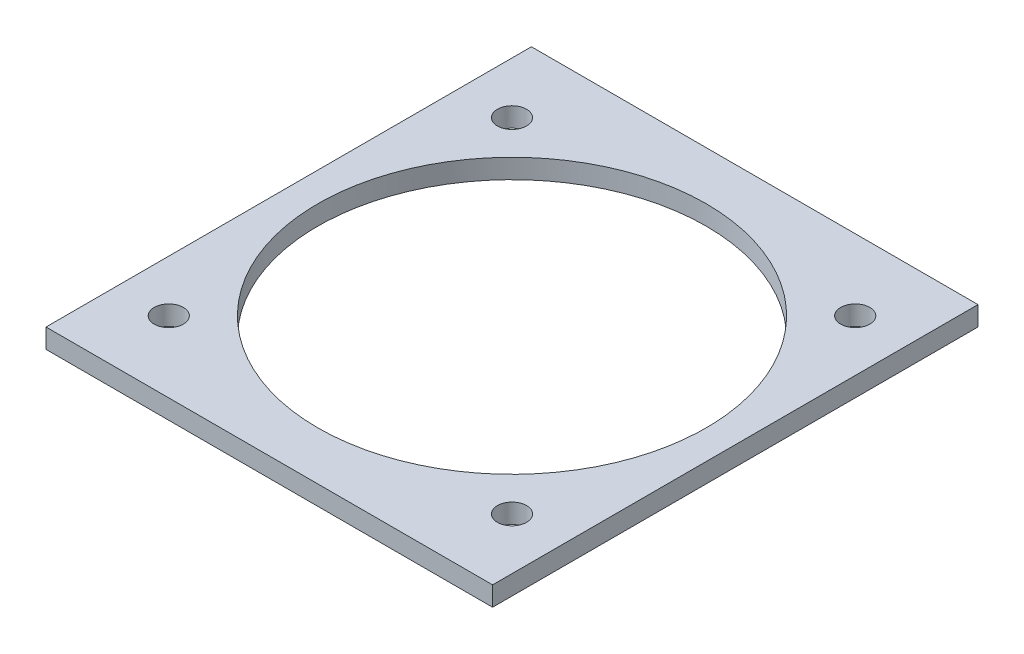
SolidWorks part; units mm, degrees
ref_plane "Front Plane" through (0, 0, 0) normal (0, 0, 1) x (1, 0, 0)
ref_plane "Top Plane" through (0, 0, 0) normal (0, 1, 0) x (1, 0, 0)
ref_plane "Right Plane" through (0, 0, 0) normal (1, 0, 0) x (0, 0, -1)
sketch "Sketch1" plane through (0, 0, 0) normal (0, 1, 0) x (1, 0, 0)
  line L1 (-23, -25) -> (23, -25)
  line L2 (-23, -25) -> (-23, 25)
  line L3 (-23, 25) -> (23, 25)
  line L4 (23, -25) -> (23, 25)
  line L5 (-23, -25) -> (23, 25) construction
  line L6 (-23, 25) -> (23, -25) construction
  point P0 (0, 0)
  dimension "D1" = 46
  dimension "D2" = 50
extrude "Boss-Extrude1" add sketch "Sketch1" along normal blind 2
sketch "Sketch2" plane through (0, 2, 0) normal (0, 1, 0) x (1, 0, 0)
  circle A0 centre (0, 0) radius 20
  dimension "D1" = 40
extrude "Cut-Extrude1" cut sketch "Sketch2" against normal through all
sketch "Sketch3" plane through (0, 2, 0) normal (0, 1, 0) x (1, 0, 0)
  line L0 (17.6777, -17.6777) -> (-17.6777, 17.6777) construction
  line L1 (-17.6777, -17.6777) -> (17.6777, 17.6777) construction
  line L2 (-9.8942, 0) -> (9.8942, 0) construction
  circle A0 centre (0, 0) radius 25 construction
  circle A5 centre (-17.6777, 17.6777) radius 1.5
  circle A6 centre (-17.6777, -17.6777) radius 1.5
  circle A7 centre (17.6777, -17.6777) radius 1.5
  circle A8 centre (17.6777, 17.6777) radius 1.5
  point P6 (0, 0)
  point P8 (0, 0)
  point P11 (0, 0)
  dimension "D1" = 50
  dimension "D2" = 90
  dimension "D4" = 3
  dimension "D3" = 45
extrude "Cut-Extrude2" cut sketch "Sketch3" against normal through all
